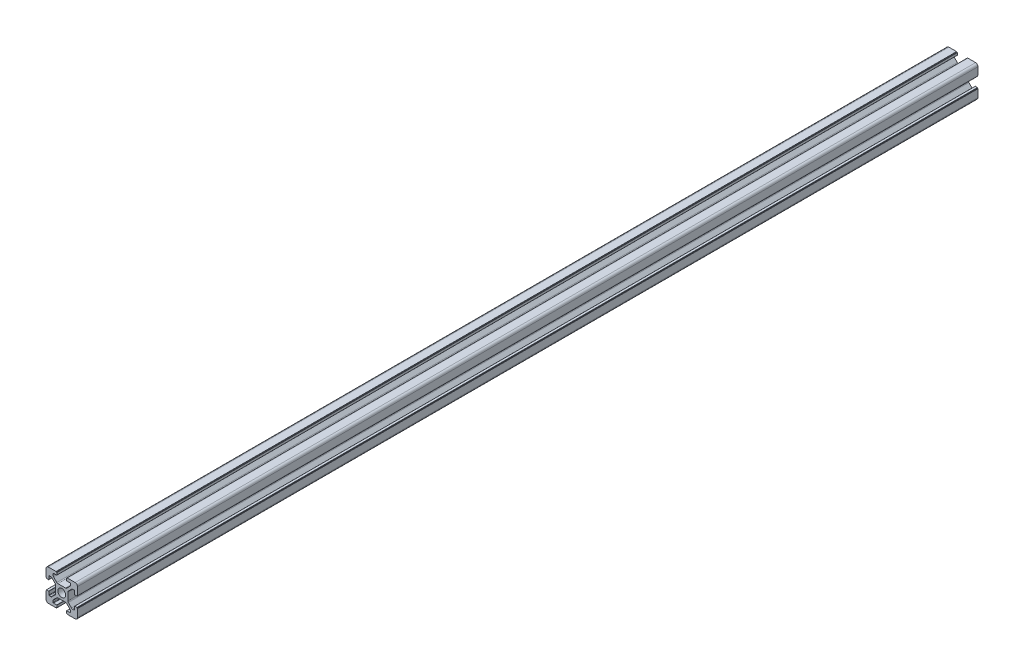
SolidWorks part; units mm, degrees
material "6063-T5"
ref_plane "前视基准面" through (0, 0, 0) normal (0, 0, 1) x (1, 0, 0)
ref_plane "上视基准面" through (0, 0, 0) normal (0, 1, 0) x (1, 0, 0)
ref_plane "右视基准面" through (0, 0, 0) normal (1, 0, 0) x (0, 0, -1)
sketch "草图1" plane through (0, 0, 0) normal (0, 0, 1) x (1, 0, 0)
  line L0 (-1.4389, 10) -> (24.3741, 10) construction
  line L1 (20, 13.6) -> (20, 20)
  line L2 (0, 0) -> (0, 6.4)
  line L3 (0, 20) -> (6.4, 20)
  line L4 (20, 0) -> (20, 6.4)
  line L5 (10, 21.5388) -> (10, -2.4017) construction
  line L6 (6.9, 18.3) -> (6.9, 19.7)
  line L7 (6.8, 18.2) -> (4.8, 18.2)
  line L8 (4.5, 17.9) -> (4.5, 16.9749)
  line L9 (4.7929, 16.2678) -> (6.8678, 14.1929)
  line L10 (7.5749, 13.9) -> (12.4251, 13.9)
  line L11 (6.8, 19.8) -> (6.4, 19.8)
  line L12 (6.4, 19.8) -> (6.4, 20)
  line L13 (0, 13.6) -> (0.2, 13.6)
  line L14 (0.2, 13.6) -> (0.2, 13.2)
  line L15 (0.3, 13.1) -> (1.7, 13.1)
  line L16 (1.8, 13.2) -> (1.8, 15.2)
  line L17 (2.1, 15.5) -> (3.0251, 15.5)
  line L18 (3.7322, 15.2071) -> (5.8071, 13.1322)
  line L19 (6.1, 12.4251) -> (6.1, 7.5749)
  line L20 (13.6, 19.8) -> (13.6, 20)
  line L21 (13.2, 19.8) -> (13.6, 19.8)
  line L22 (13.1, 18.3) -> (13.1, 19.7)
  line L23 (13.2, 18.2) -> (15.2, 18.2)
  line L24 (15.5, 17.9) -> (15.5, 16.9749)
  line L25 (15.2071, 16.2678) -> (13.1322, 14.1929)
  line L26 (0, 6.4) -> (0.2, 6.4)
  line L27 (0.2, 6.4) -> (0.2, 6.8)
  line L28 (0.3, 6.9) -> (1.7, 6.9)
  line L29 (1.8, 6.8) -> (1.8, 4.8)
  line L30 (2.1, 4.5) -> (3.0251, 4.5)
  line L31 (3.7322, 4.7929) -> (5.8071, 6.8678)
  line L32 (13.6, 20) -> (20, 20)
  line L33 (0, 13.6) -> (0, 20)
  line L34 (13.6, 0.2) -> (13.6, 0)
  line L35 (13.2, 0.2) -> (13.6, 0.2)
  line L36 (13.1, 1.7) -> (13.1, 0.3)
  line L37 (13.2, 1.8) -> (15.2, 1.8)
  line L38 (15.5, 2.1) -> (15.5, 3.0251)
  line L39 (15.2071, 3.7322) -> (13.1322, 5.8071)
  line L40 (4.5, 2.1) -> (4.5, 3.0251)
  line L41 (6.8, 1.8) -> (4.8, 1.8)
  line L42 (6.4, 0.2) -> (6.4, 0)
  line L43 (6.8, 0.2) -> (6.4, 0.2)
  line L44 (6.9, 1.7) -> (6.9, 0.3)
  line L45 (4.7929, 3.7322) -> (6.8678, 5.8071)
  line L46 (7.5749, 6.1) -> (12.4251, 6.1)
  line L47 (20, 6.4) -> (19.8, 6.4)
  line L48 (19.8, 6.4) -> (19.8, 6.8)
  line L49 (19.7, 6.9) -> (18.3, 6.9)
  line L50 (18.2, 6.8) -> (18.2, 4.8)
  line L51 (17.9, 4.5) -> (16.9749, 4.5)
  line L52 (16.2678, 4.7929) -> (14.1929, 6.8678)
  line L53 (13.9, 12.4251) -> (13.9, 7.5749)
  line L54 (16.2678, 15.2071) -> (14.1929, 13.1322)
  line L55 (17.9, 15.5) -> (16.9749, 15.5)
  line L56 (18.2, 13.2) -> (18.2, 15.2)
  line L57 (19.7, 13.1) -> (18.3, 13.1)
  line L58 (19.8, 13.6) -> (19.8, 13.2)
  line L59 (20, 13.6) -> (19.8, 13.6)
  line L60 (0, 0) -> (6.4, 0)
  line L61 (13.6, 0) -> (20, 0)
  arc A0 (6.1, 12.4251) -> (5.8071, 13.1322) centre (5.1, 12.4251) ccw
  arc A1 (7.5749, 13.9) -> (6.8678, 14.1929) centre (7.5749, 14.9) cw
  arc A2 (4.5, 16.9749) -> (4.7929, 16.2678) centre (5.5, 16.9749) ccw
  arc A3 (3.7322, 15.2071) -> (3.0251, 15.5) centre (3.0251, 14.5) ccw
  arc A4 (4.5, 17.9) -> (4.8, 18.2) centre (4.8, 17.9) cw
  arc A5 (1.8, 15.2) -> (2.1, 15.5) centre (2.1, 15.2) cw
  arc A6 (0.3, 13.1) -> (0.2, 13.2) centre (0.3, 13.2) cw
  arc A7 (6.9, 19.7) -> (6.8, 19.8) centre (6.8, 19.7) ccw
  arc A8 (1.7, 13.1) -> (1.8, 13.2) centre (1.7, 13.2) ccw
  arc A9 (6.9, 18.3) -> (6.8, 18.2) centre (6.8, 18.3) cw
  arc A10 (13.1, 19.7) -> (13.2, 19.8) centre (13.2, 19.7) cw
  arc A11 (13.1, 18.3) -> (13.2, 18.2) centre (13.2, 18.3) ccw
  arc A12 (15.5, 17.9) -> (15.2, 18.2) centre (15.2, 17.9) ccw
  arc A13 (15.5, 16.9749) -> (15.2071, 16.2678) centre (14.5, 16.9749) cw
  arc A14 (12.4251, 13.9) -> (13.1322, 14.1929) centre (12.4251, 14.9) ccw
  arc A15 (0.3, 6.9) -> (0.2, 6.8) centre (0.3, 6.8) ccw
  arc A16 (1.7, 6.9) -> (1.8, 6.8) centre (1.7, 6.8) cw
  arc A17 (1.8, 4.8) -> (2.1, 4.5) centre (2.1, 4.8) ccw
  arc A18 (3.7322, 4.7929) -> (3.0251, 4.5) centre (3.0251, 5.5) cw
  arc A19 (6.1, 7.5749) -> (5.8071, 6.8678) centre (5.1, 7.5749) cw
  arc A20 (13.1, 0.3) -> (13.2, 0.2) centre (13.2, 0.3) ccw
  arc A21 (13.1, 1.7) -> (13.2, 1.8) centre (13.2, 1.7) cw
  arc A22 (15.5, 2.1) -> (15.2, 1.8) centre (15.2, 2.1) cw
  arc A23 (15.5, 3.0251) -> (15.2071, 3.7322) centre (14.5, 3.0251) ccw
  arc A24 (12.4251, 6.1) -> (13.1322, 5.8071) centre (12.4251, 5.1) cw
  arc A25 (4.5, 2.1) -> (4.8, 1.8) centre (4.8, 2.1) ccw
  arc A26 (6.9, 0.3) -> (6.8, 0.2) centre (6.8, 0.3) cw
  arc A27 (6.9, 1.7) -> (6.8, 1.8) centre (6.8, 1.7) ccw
  arc A28 (4.5, 3.0251) -> (4.7929, 3.7322) centre (5.5, 3.0251) cw
  arc A29 (7.5749, 6.1) -> (6.8678, 5.8071) centre (7.5749, 5.1) ccw
  arc A30 (19.7, 6.9) -> (19.8, 6.8) centre (19.7, 6.8) cw
  arc A31 (18.3, 6.9) -> (18.2, 6.8) centre (18.3, 6.8) ccw
  arc A32 (18.2, 4.8) -> (17.9, 4.5) centre (17.9, 4.8) cw
  arc A33 (16.2678, 4.7929) -> (16.9749, 4.5) centre (16.9749, 5.5) ccw
  arc A34 (13.9, 7.5749) -> (14.1929, 6.8678) centre (14.9, 7.5749) ccw
  arc A35 (13.9, 12.4251) -> (14.1929, 13.1322) centre (14.9, 12.4251) cw
  arc A36 (16.2678, 15.2071) -> (16.9749, 15.5) centre (16.9749, 14.5) cw
  arc A37 (18.2, 15.2) -> (17.9, 15.5) centre (17.9, 15.2) ccw
  arc A38 (18.3, 13.1) -> (18.2, 13.2) centre (18.3, 13.2) cw
  arc A39 (19.7, 13.1) -> (19.8, 13.2) centre (19.7, 13.2) ccw
  circle A40 centre (10, 10) radius 2.5
  point P39 (0.2, 13.1)
  point P42 (6.9, 19.8)
  point P45 (1.8, 13.1)
  point P48 (6.9, 18.2)
  point P66 (10, 13.9)
  point P83 (6.1, 10)
  dimension "D19" = 1
  dimension "D20" = 1
  dimension "D21" = 0.3
  dimension "D22" = 0.1
  dimension "D23" = 5
  dimension "D1" = 20
  dimension "D2" = 20
  dimension "D3" = 10
  dimension "D4" = 10
  dimension "D5" = 1.8
  dimension "D6" = 0.5
  dimension "D7" = 1.6
  dimension "D8" = 3.1
  dimension "D9" = 6.1
  dimension "D10" = 5.5
  dimension "D11" = 3.1
  dimension "D12" = 6.1
  dimension "D13" = 5.5
  dimension "D14" = 1.8
  dimension "D15" = 0.5
  dimension "D16" = 1.5
  dimension "D17" = 45
  dimension "D18" = 1.6
extrude "凸台-拉伸1" add sketch "草图1" along normal blind 572
fillet "圆角1" radius 1.5 4 edges at (20, 0, 286) (0, 0, 286) (0, 20, 286) (20, 20, 286)
